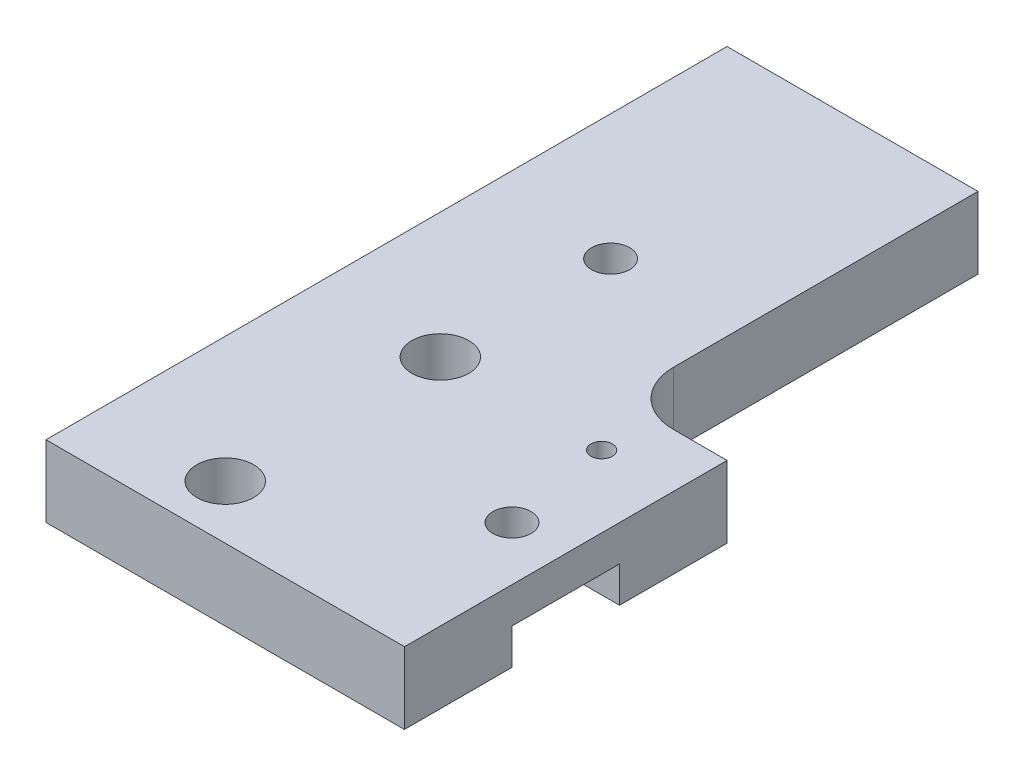
SolidWorks part; units mm, degrees
material "6061-T6 (SS)"
ref_plane "Front" through (0, 0, 0) normal (0, 0, 1) x (1, 0, 0)
ref_plane "Top" through (0, 0, 0) normal (0, 1, 0) x (1, 0, 0)
ref_plane "Right" through (0, 0, 0) normal (1, 0, 0) x (0, 0, -1)
sketch "Sketch1" plane through (0, 0, 0) normal (0, 1, 0) x (1, 0, 0)
  line L1 (-31.75, -28.575) -> (31.75, -28.575)
  line L2 (-31.75, -28.575) -> (-31.75, 28.575)
  line L3 (-31.75, 28.575) -> (31.75, 28.575)
  line L4 (31.75, -28.575) -> (31.75, 28.575)
  line L5 (-31.75, -28.575) -> (31.75, 28.575) construction
  line L6 (-31.75, 28.575) -> (31.75, -28.575) construction
  point P0 (0, 0)
  dimension "D1" = 63.5
  dimension "D2" = 57.15
extrude "Boss-Extrude1" add sketch "Sketch1" along normal blind 12.7
sketch "Sketch2" plane through (0, 0, 0) normal (0, -1, 0) x (1, 0, 0)
  line L0 (31.75, 28.575) -> (31.75, -28.575) construction
  line L1 (-31.75, -9.525) -> (31.75, -9.525)
  line L2 (-31.75, -9.525) -> (-31.75, 9.525)
  line L3 (-31.75, 9.525) -> (31.75, 9.525)
  line L4 (31.75, -9.525) -> (31.75, 9.525)
  line L5 (-31.75, -9.525) -> (31.75, 9.525) construction
  line L6 (-31.75, 9.525) -> (31.75, -9.525) construction
  point P0 (0, 0)
  dimension "D1" = 19.05
extrude "Cut-Extrude1" cut sketch "Sketch2" against normal blind 6.35
sketch "Sketch3" plane through (0, 0, 0) normal (0, -1, 0) x (1, 0, 0)
  line L0 (-31.75, 28.575) -> (31.75, 28.575) construction
  line L1 (3.175, 28.575) -> (15.875, 28.575)
  line L2 (3.175, 28.575) -> (3.175, -28.575)
  line L3 (3.175, -28.575) -> (15.875, -28.575)
  line L4 (15.875, 28.575) -> (15.875, -28.575)
  line L5 (31.75, -28.575) -> (-31.75, -28.575) construction
  line L6 (31.75, 28.575) -> (31.75, 9.525) construction
  dimension "D1" = 12.7
  dimension "D2" = 15.875
extrude "Cut-Extrude2" [suppressed] cut sketch "Sketch3" against normal up to surface (6.35 mm away)
sketch "Sketch4" plane through (0, 6.35, 0) normal (0, -1, 0) x (1, 0, 0)
  line L0 (31.75, 0) -> (22.225, 0) construction
  line L1 (31.75, -9.525) -> (31.75, 9.525) construction
  line L2 (9.525, 28.575) -> (9.525, 19.05) construction
  dimension "D1" = 9.525
sketch "Sketch7" plane through (0, 0, 0) normal (0, 1, 0) x (1, 0, 0)
  line L0 (-9.525, 28.575) -> (-9.525, 19.05) construction
  line L1 (31.75, 28.575) -> (-31.75, 28.575) construction
  line L2 (-9.525, 19.05) -> (-9.525, 9.525) construction
  line L3 (-9.525, -19.05) -> (-9.525, -28.575) construction
  line L4 (-31.75, -28.575) -> (31.75, -28.575) construction
  line L5 (-31.75, 28.575) -> (-31.75, -28.575) construction
  line L10 (-31.75, 9.525) -> (31.75, 9.525) construction
  dimension "D2" = 22.225
hole_wizard "3/8 Clearance Hole1" positions "Sketch9" profile "Sketch8" hole size "3/8" standard "ANSI Inch" end condition through all
sketch "Sketch9" plane through (0, 12.7, 0) normal (0, 1, 0) x (1, 0, 0)
  point P0 (-9.525, 19.05)
  point P3 (-9.525, -19.05)
sketch "Sketch8" plane through (-9.525, 12.7, -19.05) normal (1, 0, 0) x (0, 0, 1)
  line L0 (0, 0) -> (0, 12.7)
  line L1 (0, 12.7) -> (5.0419, 12.7)
  line L2 (5.0419, 12.7) -> (5.0419, 0)
  line L5 (5.0419, 0) -> (0, 0)
  line L11 (0, -6.35) -> (0, 107.95) construction
  dimension "Thru Hole Dia." = 10.0838
  dimension "Thru Hole Depth" = 12.7
sketch "Sketch10" plane through (0, 0, -28.575) normal (0, 0, -1) x (-1, 0, 0)
  line L1 (31.75, 12.7) -> (-31.75, 12.7)
  line L2 (31.75, 12.7) -> (31.75, 0)
  line L3 (31.75, 0) -> (-31.75, 0)
  line L4 (-31.75, 12.7) -> (-31.75, 0)
extrude "Boss-Extrude2" add sketch "Sketch10" along normal blind 63.5
sketch "Sketch11" plane through (0, 0, 0) normal (0, -1, 0) x (1, 0, 0)
  line L0 (31.75, -92.075) -> (-31.75, -92.075) construction
  line L1 (-19.05, -92.075) -> (0, -92.075)
  line L2 (-19.05, -92.075) -> (-19.05, -31.75)
  line L3 (-19.05, -31.75) -> (0, -31.75)
  line L4 (0, -92.075) -> (0, -31.75)
  line L5 (0, -39.2296) -> (-9.525, -39.2296) construction
  line L7 (-31.75, -9.525) -> (-31.75, 9.525) construction
  line L8 (-9.525, -28.575) -> (-9.525, -39.2296) construction
  line L9 (-9.525, -28.575) -> (-9.525, -19.05) construction
  circle A0 centre (-9.525, -19.05) radius 5.0419 construction
  dimension "D1" = 9.525
  dimension "D2" = 12.7
extrude "Cut-Extrude3" cut sketch "Sketch11" against normal up to surface (6.35 mm away) up to face at (0, 6.35, 0)
fillet "Fillet1" radius 4.7625 2 edges at (0, 3.175, -31.75) (-19.05, 3.175, -31.75)
sketch "Sketch12" plane through (0, 6.35, 0) normal (0, -1, 0) x (1, 0, 0)
  line L0 (0, -36.5125) -> (-9.525, -36.5125) construction
  line L1 (-9.525, -36.5125) -> (-9.525, -49.2125) construction
  arc A0 (0, -36.5125) -> (-4.7625, -31.75) centre (-4.7625, -36.5125) ccw construction
  dimension "D1" = 9.525
  dimension "D2" = 12.7
hole_wizard "1/4 Clearance Hole1" positions "Sketch6" profile "Sketch5" hole size "1/4" standard "ANSI Inch" end condition through all
sketch "Sketch6" plane through (0, 6.35, 0) normal (0, -1, 0) x (-1, 0, 0)
  point P3 (-22.225, 0)
  point P9 (9.525, 49.2125)
sketch "Sketch5" plane through (22.225, 6.35, 0) normal (1, 0, 0) x (0, 0, -1)
  line L0 (0, 0) -> (0, 6.35)
  line L1 (0, 6.35) -> (3.3782, 6.35)
  line L2 (3.3782, 6.35) -> (3.3782, 0)
  line L5 (3.3782, 0) -> (0, 0)
  line L11 (0, -6.35) -> (0, 107.95) construction
  dimension "Thru Hole Dia." = 6.7564
  dimension "Thru Hole Depth" = 6.35
sketch "Sketch13" plane through (0, 0, 0) normal (0, -1, 0) x (1, 0, 0)
  line L0 (12.7, -92.075) -> (12.7, -28.575)
  line L1 (31.75, -92.075) -> (0, -92.075) construction
  line L2 (12.7, -28.575) -> (31.75, -28.575)
  line L3 (31.75, -9.525) -> (31.75, -92.075) construction
  line L4 (31.75, -28.575) -> (31.75, -92.075)
  line L5 (31.75, -92.075) -> (12.7, -92.075)
  line L6 (-31.75, 28.575) -> (31.75, 28.575) construction
  dimension "D1" = 19.05
  dimension "D2" = 57.15
extrude "Cut-Extrude5" cut sketch "Sketch13" against normal through all
fillet "Fillet2" radius 9.525 1 edges at (12.7, 6.35, -28.575)
sketch "Sketch14" plane through (0, 12.7, 0) normal (0, 1, 0) x (1, 0, 0)
  line L0 (31.75, 19.05) -> (19.05, 19.05) construction
  line L1 (31.75, -28.575) -> (31.75, 28.575) construction
  line L2 (-31.75, -28.575) -> (31.75, -28.575) construction
  dimension "D1" = 12.7
  dimension "D2" = 47.625
hole_wizard "#10-24 Tapped Hole1" positions "Sketch16" profile "Sketch15" tap size "#10-24" standard "ANSI Inch" end condition through all
sketch "Sketch16" plane through (0, 12.7, 0) normal (0, 1, 0) x (1, 0, 0)
  point P0 (19.05, 19.05)
sketch "Sketch15" plane through (19.05, 12.7, -19.05) normal (1, 0, 0) x (0, 0, 1)
  line L0 (0, 0) -> (0, 12.7)
  line L1 (0, 12.7) -> (1.8986, 12.7)
  line L2 (1.8986, 12.7) -> (1.8986, 0)
  line L5 (1.8986, 0) -> (0, 0)
  line L11 (0, -6.35) -> (0, 107.95) construction
  dimension "Thru Tap Drill Dia." = 3.7973
  dimension "Thru Tap Drill Depth" = 12.7
cosmetic thread "Hole Thread1" parameters "D2"=4.826
